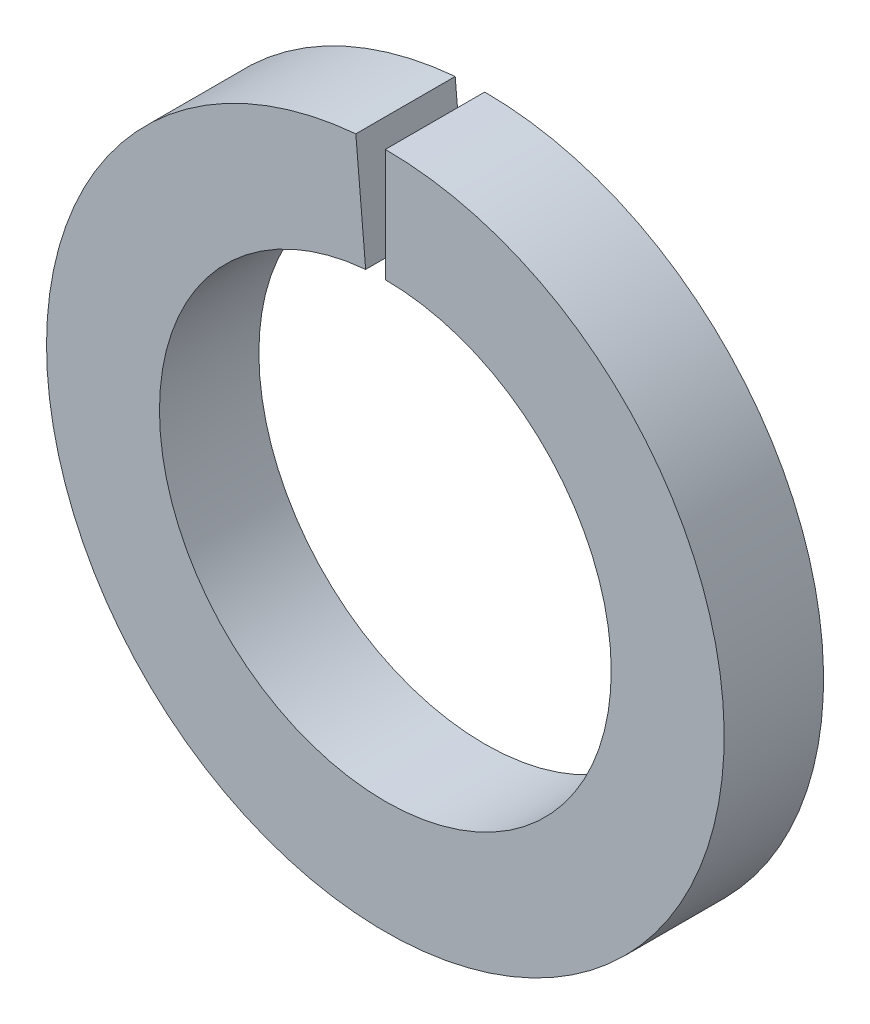
SolidWorks part; units mm, degrees
ref_plane "前视基准面" through (0, 0, 0) normal (0, 0, 1) x (1, 0, 0)
ref_plane "上视基准面" through (0, 0, 0) normal (0, 1, 0) x (1, 0, 0)
ref_plane "右视基准面" through (0, 0, 0) normal (1, 0, 0) x (0, 0, -1)
sketch "草图1" plane through (0, 0, 0) normal (0, 0, 1) x (1, 0, 0)
  line L0 (0, 5) -> (0, 7.5)
  line L1 (0, 0) -> (-0.6537, 7.4715) construction
  line L3 (-0.6537, 7.4715) -> (-0.4358, 4.981)
  circle A0 centre (0, 0) radius 7.5 construction
  circle A1 centre (0, 0) radius 5 construction
  arc A3 (0, 5) -> (-0.4358, 4.981) centre (0, 0) cw
  arc A4 (-0.6537, 7.4715) -> (0, 7.5) centre (0, 0) ccw
  dimension "D1" = 15
  dimension "D2" = 10
extrude "凸台-拉伸1" add sketch "草图1" along normal blind 2.2 contours A0
